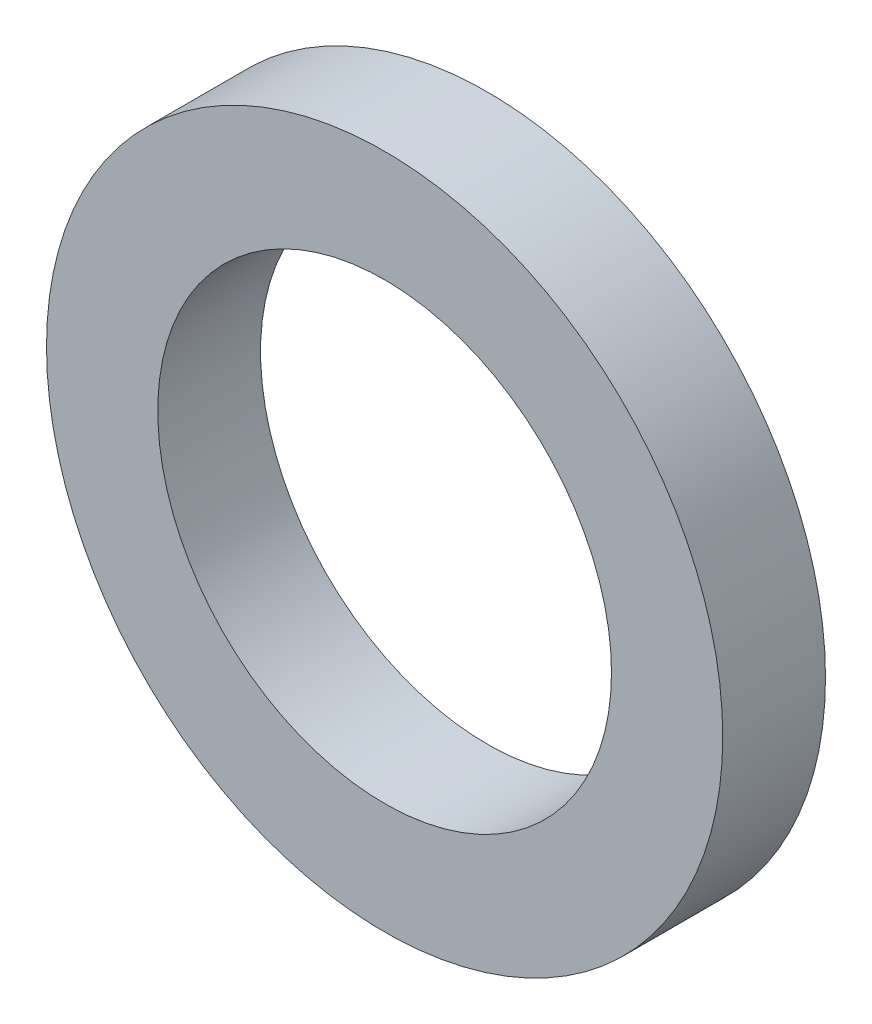
SolidWorks part; units mm, degrees
ref_plane "Front Plane" through (0, 0, 0) normal (0, 0, 1) x (1, 0, 0)
ref_plane "Top Plane" through (0, 0, 0) normal (0, 1, 0) x (1, 0, 0)
ref_plane "Right Plane" through (0, 0, 0) normal (1, 0, 0) x (0, 0, -1)
sketch "Sketch2" plane through (0, 0, 0) normal (0, 0, 1) x (1, 0, 0)
  circle A0 centre (7.62, -54.61) radius 4.318
  circle A1 centre (7.62, -54.61) radius 6.4362
  dimension "D1" = 8.636
extrude "Boss-Extrude1" add sketch "Sketch2" along normal blind 1.9558
